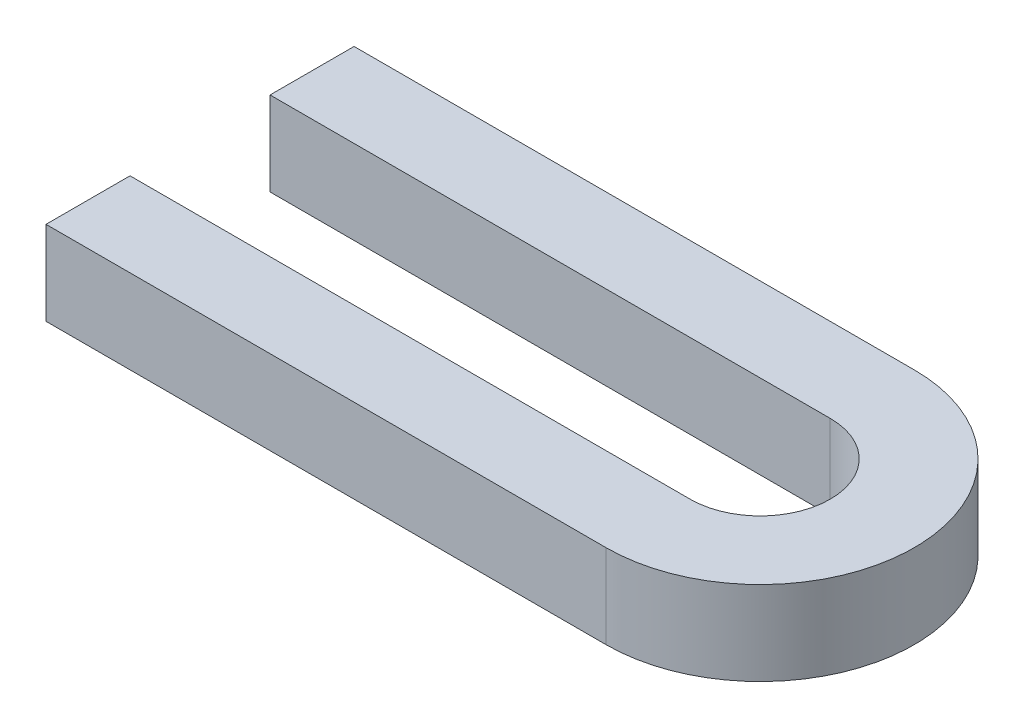
SolidWorks part; units mm, degrees
ref_plane "前视基准面" through (0, 0, 0) normal (0, 0, 1) x (1, 0, 0)
ref_plane "上视基准面" through (0, 0, 0) normal (0, 1, 0) x (1, 0, 0)
ref_plane "右视基准面" through (0, 0, 0) normal (1, 0, 0) x (0, 0, -1)
other "Configuration Table"
sketch "草图1" plane through (0, 0, 0) normal (0, 1, 0) x (1, 0, 0)
  line L0 (0, 0) -> (-10.1449, 0) construction
  line L1 (0, 2.5) -> (-20, 2.5)
  line L2 (0, -2.5) -> (-20, -2.5)
  line L3 (0, -5.5) -> (-20, -5.5)
  line L4 (0, 5.5) -> (-20, 5.5)
  line L5 (-20, 5.5) -> (-20, 2.5)
  line L6 (-20, -2.5) -> (-20, -5.5)
  arc A0 (0, 2.5) -> (0, -2.5) centre (0, 0) cw
  arc A1 (0, 5.5) -> (0, -5.5) centre (0, 0) cw
  dimension "D1" = 2.5
  dimension "D2" = 20
  dimension "D3" = 2.5
  dimension "D4" = 3
extrude "凸台-拉伸1" add sketch "草图1" along normal blind 3
